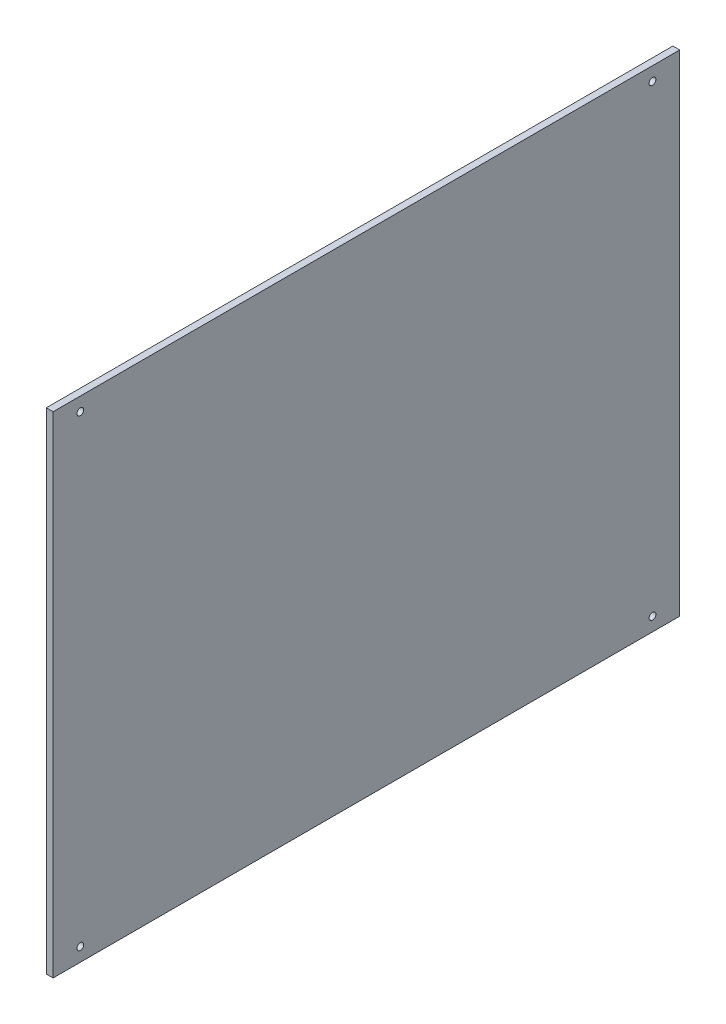
SolidWorks part; units mm, degrees
ref_plane "Front Plane" through (0, 0, 0) normal (0, 0, 1) x (1, 0, 0)
ref_plane "Top Plane" through (0, 0, 0) normal (0, 1, 0) x (1, 0, 0)
ref_plane "Right Plane" through (0, 0, 0) normal (1, 0, 0) x (0, 0, -1)
sketch "Sketch2" plane through (0, 0, 0) normal (1, 0, 0) x (0, 0, -1)
  line L1 (146.05, 114.3) -> (-146.05, 114.3)
  line L2 (146.05, 114.3) -> (146.05, -114.3)
  line L3 (146.05, -114.3) -> (-146.05, -114.3)
  line L4 (-146.05, 114.3) -> (-146.05, -114.3)
  line L5 (146.05, 114.3) -> (-146.05, -114.3) construction
  line L6 (146.05, -114.3) -> (-146.05, 114.3) construction
  point P0 (0, 0)
  dimension "D1" = 228.6
  dimension "D2" = 292.1
extrude "Boss-Extrude1" add sketch "Sketch2" along normal blind 3.175
sketch "Sketch3" plane through (3.175, 0, 0) normal (1, 0, 0) x (0, 0, -1)
  line L0 (-133.35, -107.95) -> (146.05, -107.95) construction
  line L1 (146.05, -114.3) -> (146.05, 114.3) construction
  line L2 (-146.05, -114.3) -> (146.05, -114.3) construction
  line L3 (-146.05, 114.3) -> (-146.05, -114.3) construction
  line L4 (-133.35, -107.95) -> (-184.15, -107.95) construction
  circle A0 centre (-133.35, -107.95) radius 1.5875
  dimension "D2" = 3.175
  dimension "D1" = 6.35
  dimension "D3" = 12.7
  dimension "D5" = 50.8
extrude "Cut-Extrude1" cut sketch "Sketch3" against normal through all
mirror "Mirror1" about plane through (0, 0, 0) normal (0, 1, 0) of "Cut-Extrude1"
mirror "Mirror2" about plane through (0, 0, 0) normal (0, 0, 1) of "Mirror1", "Cut-Extrude1"
